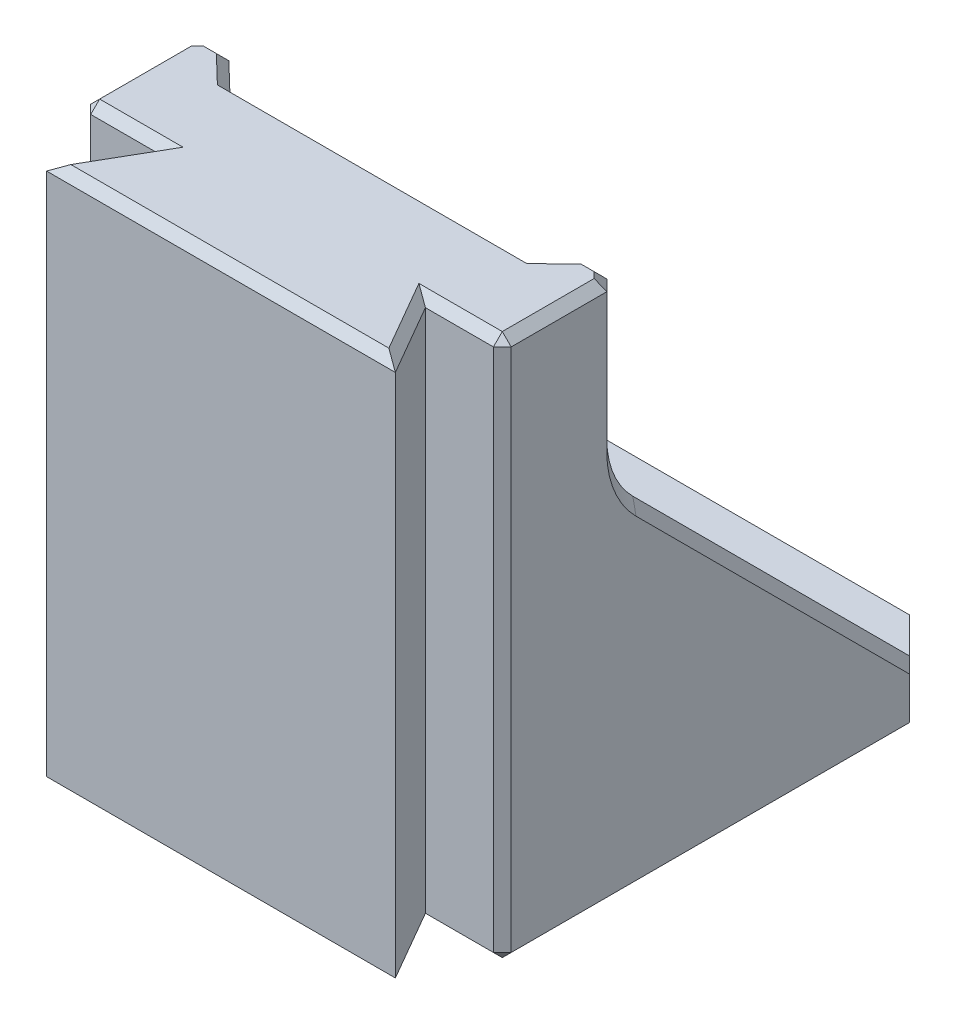
SolidWorks part; units mm, degrees
material "ABS"
ref_plane "Front Plane" through (0, 0, 0) normal (0, 0, 1) x (1, 0, 0)
ref_plane "Top Plane" through (0, 0, 0) normal (0, 1, 0) x (1, 0, 0)
ref_plane "Right Plane" through (0, 0, 0) normal (1, 0, 0) x (0, 0, -1)
sketch "Sketch1" plane through (0, 0, 0) normal (0, 1, 0) x (1, 0, 0)
  line L0 (-21.15, 17.15) -> (-17.15, 21.15)
  line L1 (-17, -21.15) -> (17, -21.15)
  line L2 (-21.15, -17.15) -> (-21.15, 17.15)
  line L3 (-17.15, 21.15) -> (17.15, 21.15)
  line L4 (21.15, -17.15) -> (21.15, 17.15)
  line L5 (-21.15, -21.15) -> (21.15, 21.15) construction
  line L6 (-21.15, 21.15) -> (21.15, -21.15) construction
  line L7 (-21.15, -17.15) -> (-17, -21.15)
  line L8 (17, -21.15) -> (21.15, -17.15)
  line L9 (17.15, 21.15) -> (21.15, 17.15)
  circle A0 centre (-15.5, 15.5) radius 1.5
  circle A1 centre (15.5, 15.5) radius 1.5
  circle A2 centre (15.5, -15.5) radius 1.5
  circle A3 centre (-15.5, -15.5) radius 1.5
  circle A4 centre (0, 0) radius 11.5
  point P0 (0, 0)
  point P22 (0, -21.15)
  dimension "D3" = 3
  dimension "D4" = 3
  dimension "D9" = 3
  dimension "D10" = 3
  dimension "D12" = 23
  dimension "D1" = 42.3
  dimension "D2" = 42.3
  dimension "D13" = 34
  dimension "D11" = 31
extrude "Bracket Face Extrude" add sketch "Sketch1" along normal blind 5
sketch "Sketch5" plane through (0, 0, 0) normal (0, 1, 0) x (1, 0, 0)
  line L0 (-23.65, -18.2126) -> (-23.65, -31.15)
  line L1 (-23.65, -31.15) -> (23.65, -31.15)
  line L2 (23.65, -31.15) -> (23.65, -18.2126)
  line L16 (-23.65, 18.1855) -> (-23.65, -18.2126)
  line L17 (-23.65, -18.2126) -> (-18.0087, -23.65)
  line L18 (-18.0087, -23.65) -> (18.0087, -23.65)
  line L19 (18.0087, -23.65) -> (23.65, -18.2126)
  line L20 (23.65, -18.2126) -> (23.65, 18.1855)
  line L21 (23.65, 18.1855) -> (18.1855, 23.65)
  line L22 (18.1855, 23.65) -> (-18.1855, 23.65)
  line L23 (-18.1855, 23.65) -> (-23.65, 18.1855)
  line L24 (-23.65, 14.65) -> (-23.65, -18.2126)
  line L25 (-23.65, -18.2126) -> (-18.0087, -23.65) construction
  line L26 (-18.0087, -23.65) -> (18.0087, -23.65) construction
  line L27 (18.0087, -23.65) -> (23.65, -18.2126) construction
  line L28 (23.65, -18.2126) -> (23.65, 14.65)
  line L29 (23.65, 18.1855) -> (18.1855, 23.65) construction
  line L30 (18.1855, 23.65) -> (-18.1855, 23.65) construction
  line L31 (-18.1855, 23.65) -> (-23.65, 18.1855) construction
  line L32 (-21.15, 17.15) -> (-23.65, 14.65)
  line L33 (21.15, 17.15) -> (23.65, 14.65)
  line L34 (-23.65, 18.1855) -> (-23.65, 14.65) construction
  line L35 (23.65, 14.65) -> (23.65, 18.1855) construction
  line L40 (-21.15, 17.15) -> (-21.15, -17.15)
  line L41 (-21.15, -17.15) -> (-17, -21.15)
  line L42 (-17, -21.15) -> (17, -21.15)
  line L43 (17, -21.15) -> (21.15, -17.15)
  line L44 (21.15, -17.15) -> (21.15, 17.15)
  line L45 (21.15, 17.15) -> (17.15, 21.15)
  line L46 (17.15, 21.15) -> (-17.15, 21.15)
  line L47 (-17.15, 21.15) -> (-21.15, 17.15)
  line L48 (-21.15, 17.15) -> (-21.15, -17.15)
  line L49 (-21.15, -17.15) -> (-17, -21.15)
  line L50 (-17, -21.15) -> (17, -21.15)
  line L51 (17, -21.15) -> (21.15, -17.15)
  line L52 (21.15, -17.15) -> (21.15, 17.15)
  line L53 (21.15, 17.15) -> (17.15, 21.15) construction
  line L54 (17.15, 21.15) -> (-17.15, 21.15) construction
  line L55 (-17.15, 21.15) -> (-21.15, 17.15) construction
  dimension "D3" = 10
  dimension "D1" = 2.5
  dimension "D2" = 0
extrude "Bracket Body Extrude" add sketch "Sketch5" along normal blind 61
sketch "Sketch6" plane through (0, 0, 0) normal (1, 0, 0) x (0, 0, -1)
  line L0 (17.15, 5) -> (-15.2211, 37.3711)
  line L1 (-18.15, 44.4421) -> (-18.15, 61)
  line L3 (-18.15, 61) -> (17.15, 61)
  line L4 (17.15, 61) -> (17.15, 5)
  line L6 (-31.15, 61) -> (-31.15, 0) construction
  line L7 (-31.15, 61) -> (14.65, 61) construction
  arc A0 (-15.2211, 37.3711) -> (-18.15, 44.4421) centre (-8.15, 44.4421) cw
  dimension "D3" = 10
  dimension "D1" = 13
  dimension "D2" = 45
extrude "Bracket Side Trim" cut sketch "Sketch6" against normal through all both and the other way through all
chamfer "Bracket Side Edge Chamfer" distance 1.25 angle 45 6 edges at (-23.65, 52.7211, 18.15) (-23.65, 40.6153, 17.3888) (-23.65, 22.4355, 0.2855) (23.65, 52.7211, 18.15) (23.65, 40.6153, 17.3888) (23.65, 22.4355, 0.2855)
chamfer "Bracket Mount Hole Chamfer" distance 0.75 angle 45 4 edges at (-15.5, 0, 17) (-15.5, 0, -14) (15.5, 0, 17) (15.5, 0, -14)
sketch "Sketch9" plane through (0, 0, 0) normal (0, 1, 0) x (1, 0, 0)
  line L0 (-15, -31.15) -> (-19.6188, -39.15)
  line L1 (-19.6188, -39.15) -> (19.6188, -39.15)
  line L2 (19.6188, -39.15) -> (15, -31.15)
  line L3 (15, -31.15) -> (-15, -31.15)
  line L4 (-23.65, -31.15) -> (23.65, -31.15) construction
  point P8 (0, -39.15)
  dimension "D1" = 60
  dimension "D3" = 8
  dimension "D4" = 30
extrude "Slide Tab Extrude" add sketch "Sketch9" along normal up to surface (61 mm away) up to face at (0, 61, 21.6)
chamfer "Bracket Face Chamfer" distance 1 angle 45 26 edges at (17.3094, 61, 35.15) (17.3094, 0, 35.15) (-17.3094, 61, 35.15) (-17.3094, 0, 35.15) (-19.325, 0, 31.15) (-19.325, 61, 31.15) (19.325, 0, 31.15) (19.325, 61, 31.15) (-23.65, 0, 8.25) (23.65, 0, 8.25) (20.4, 0, -17.9) (-20.4, 0, -17.9) (0, 0, -21.15) (0, 61, 39.15) (0, 0, 39.15) (-18.5562, 61, 19.65) (0, 61, 21.15) (18.5562, 61, 19.65) (21.2562, 61, 18.15) (23.025, 61, 18.775) (23.65, 61, 25.275) (-21.2562, 61, 18.15) (-23.025, 61, 18.775) (-23.65, 61, 25.275) (23.65, 30.5, 31.15) (-23.65, 30.5, 31.15)
sketch "Sketch15" [suppressed] plane through (0, 0, 0) normal (0, -1, 0) x (-1, 0, 0)
  circle A4 centre (0, 0) radius 13.6
  circle A5 centre (0, 0) radius 11.5 construction
  circle A6 centre (0, 0) radius 11.5 construction
  dimension "D4" = 27.2
extrude "Rotary Potentiometer Mount" [suppressed] add sketch "Sketch15" along normal blind 4
sketch "Sketch16" [suppressed] plane through (0, -4, 0) normal (0, -1, 0) x (1, 0, 0)
  circle A2 centre (0, 0) radius 6
  dimension "D4" = 12
extrude "Rotary Potentiometer Mounting Holes" [suppressed] cut sketch "Sketch16" against normal through all
chamfer "Pot Mount Main Chamfer" [suppressed] distance 4 angle 45
chamfer "Main Through Hole Chamfers" [suppressed] distance 1 angle 45
